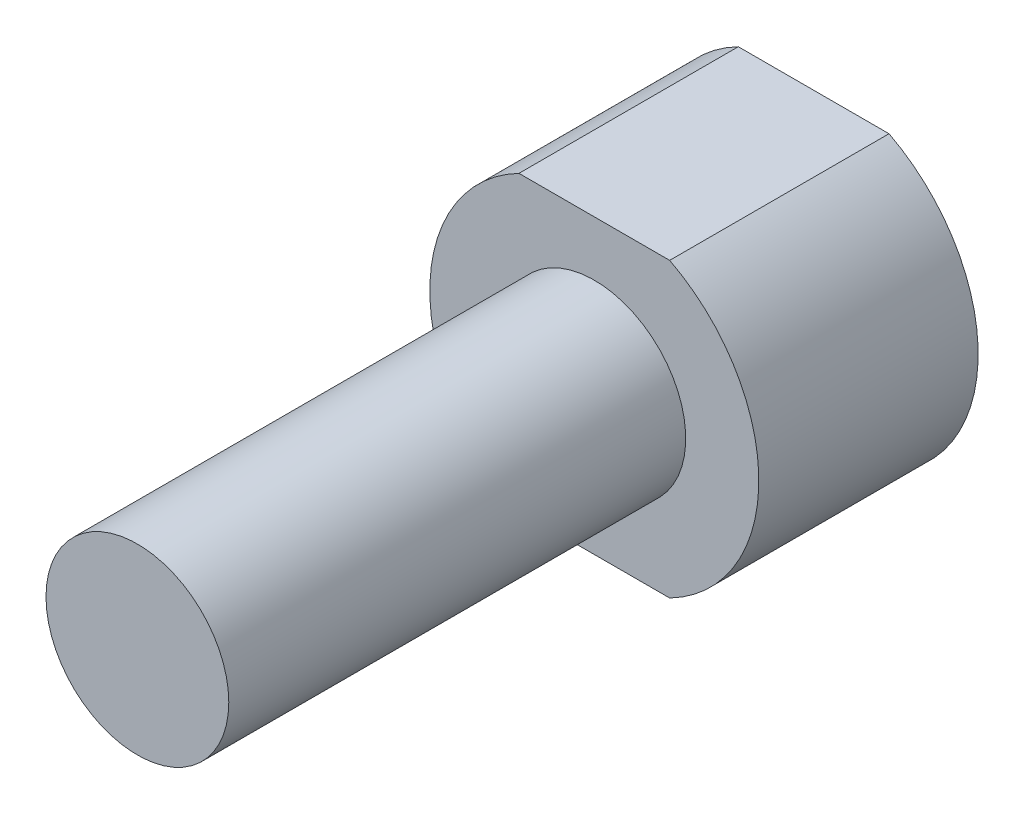
SolidWorks part; units mm, degrees
ref_plane "Plan de face" through (0, 0, 0) normal (0, 0, 1) x (1, 0, 0)
ref_plane "Plan de dessus" through (0, 0, 0) normal (0, 1, 0) x (1, 0, 0)
ref_plane "Plan de droite" through (0, 0, 0) normal (1, 0, 0) x (0, 0, -1)
sketch "Esquisse1" plane through (0, 0, 0) normal (0, 0, 1) x (1, 0, 0)
  line L0 (-12.5229, 8) -> (-9, 8) construction
  line L1 (-9, -8) -> (-12.5229, -8) construction
  line L2 (-12.5229, 0) -> (13.9382, 0) construction
  circle A0 centre (0, 0) radius 9 construction
  point P9 (-9, 8)
  line B0 (-4.1231, 8) -> (4.1231, 8)
  line B1 (4.1231, -8) -> (-4.1231, -8)
  arc B2 (4.1231, 8) -> (4.1231, -8) centre (0, 0) cw
  arc B3 (-4.1231, 8) -> (-4.1231, -8) centre (0, 0) ccw
  dimension "D1" = 18
  dimension "D2" = 16
sketch_block_instance "Bloc1-1"
sketch_block "Bloc1"
extrude "Boss.-Extru.1" add sketch "Esquisse1" along normal blind 12
sketch "Esquisse2" plane through (0, 0, 12) normal (0, 0, 1) x (1, 0, 0)
  circle A0 centre (0, 0) radius 5
  dimension "D1" = 10
extrude "Boss.-Extru.2" add sketch "Esquisse2" along normal blind 25
